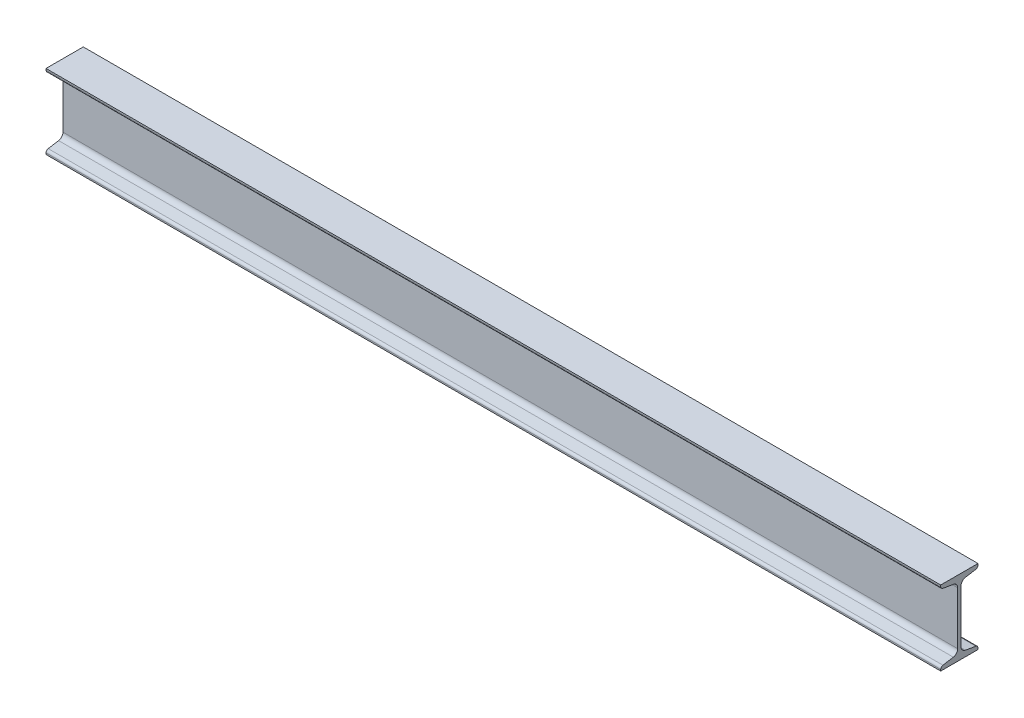
SolidWorks part; units mm, degrees
ref_plane "Front" through (0, 0, 0) normal (0, 0, 1) x (1, 0, 0)
ref_plane "Top" through (0, 0, 0) normal (0, 1, 0) x (1, 0, 0)
ref_plane "Right" through (0, 0, 0) normal (1, 0, 0) x (0, 0, -1)
sketch "Sketch1" plane through (0, 0, 0) normal (0, 1, 0) x (1, 0, 0)
  line L0 (0, 0) -> (1200, 0)
  dimension "D1" = 1200
other "Sb beam 100 X 8(1)"
ref_plane "Plane1" through (0, 0, 0) normal (1, 0, 0) x (0, 0, -1)
sketch "Sketch11" plane through (0, 0, 0) normal (1, 0, 0) x (0, 0, -1)
  line L0 (-25, -50) -> (-25, -48.0607)
  line L1 (-22.0754, -44.6083) -> (-8.0991, -42.2787)
  line L2 (-2.25, -35.374) -> (-2.25, 35.374)
  line L3 (-8.0991, 42.2787) -> (-22.0754, 44.6083)
  line L4 (-25, 48.0607) -> (-25, 50)
  line L5 (-25, 50) -> (25, 50)
  line L6 (25, 50) -> (25, 48.0607)
  line L7 (22.0754, 44.6083) -> (8.0991, 42.2787)
  line L8 (2.25, 35.374) -> (2.25, -35.374)
  line L9 (8.0991, -42.2787) -> (22.0754, -44.6083)
  line L10 (25, -48.0607) -> (25, -50)
  line L11 (25, -50) -> (-25, -50)
  line L15 (-2.25, 0) -> (2.25, 0) construction
  arc A0 (-8.0991, -42.2787) -> (-2.25, -35.374) centre (-9.25, -35.374) ccw
  arc A1 (-2.25, 35.374) -> (-8.0991, 42.2787) centre (-9.25, 35.374) ccw
  arc A2 (8.0991, 42.2787) -> (2.25, 35.374) centre (9.25, 35.374) ccw
  arc A3 (2.25, -35.374) -> (8.0991, -42.2787) centre (9.25, -35.374) ccw
  arc A4 (-22.0754, 44.6083) -> (-25, 48.0607) centre (-21.5, 48.0607) cw
  arc A5 (22.0754, 44.6083) -> (25, 48.0607) centre (21.5, 48.0607) ccw
  arc A6 (-25, -48.0607) -> (-22.0754, -44.6083) centre (-21.5, -48.0607) cw
  arc A7 (25, -48.0607) -> (22.0754, -44.6083) centre (21.5, -48.0607) ccw
  point P1 (0, 50)
  point P8 (0, -50)
  point P21 (0, 0)
  point P34 (0, 0)
  dimension "RI" = 7
  dimension "D3" = 3.5
  dimension "BF" = 50
  dimension "D2" = 9.463
  dimension "DEPTH" = 100
  dimension "TW" = 4.5
  dimension "D1" = 70.748
